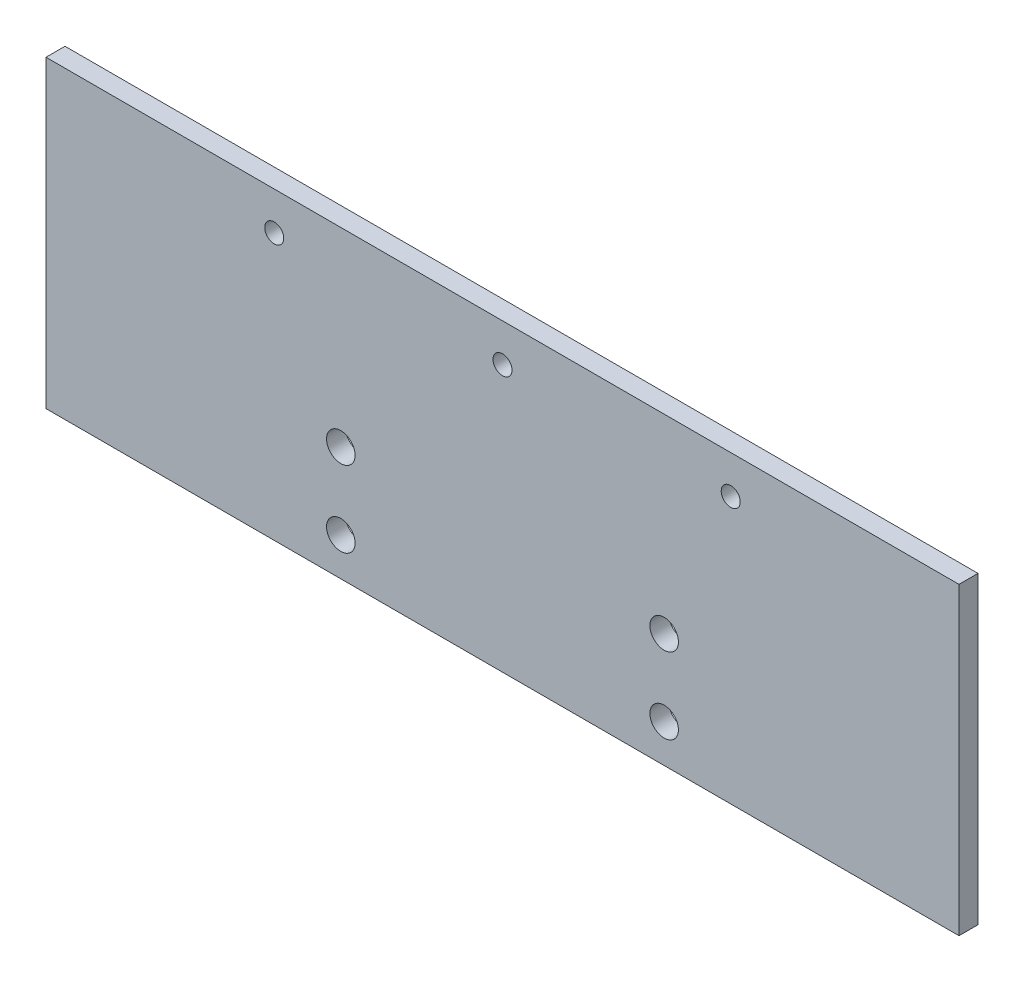
SolidWorks part; units mm, degrees
ref_plane "Front Plane" through (0, 0, 0) normal (0, 0, 1) x (1, 0, 0)
ref_plane "Top Plane" through (0, 0, 0) normal (0, 1, 0) x (1, 0, 0)
ref_plane "Right Plane" through (0, 0, 0) normal (1, 0, 0) x (0, 0, -1)
sketch "Sketch1" plane through (0, 0, 0) normal (0, 0, 1) x (1, 0, 0)
  line L1 (0, 0) -> (304.8, 0)
  line L2 (0, 0) -> (0, -101.6)
  line L3 (0, -101.6) -> (304.8, -101.6)
  line L4 (304.8, 0) -> (304.8, -101.6)
  dimension "D1" = 304.8
  dimension "D2" = 101.6
extrude "Boss-Extrude1" add sketch "Sketch1" along normal blind 6.35
sketch "Sketch2" plane through (0, 0, 6.35) normal (0, 0, 1) x (1, 0, 0)
  line L0 (304.8, 0) -> (0, 0) construction
  line L1 (0, 0) -> (0, -101.6) construction
  line L2 (0, -101.6) -> (304.8, -101.6) construction
  circle A0 centre (76.2, -12.7) radius 3.175
  circle A1 centre (152.4, -12.7) radius 3.175
  circle A2 centre (228.6, -12.7) radius 3.175
  circle A3 centre (98.425, -63.5) radius 4.7625
  circle A4 centre (206.375, -63.5) radius 4.7625
  circle A5 centre (98.425, -88.9) radius 4.7625
  circle A6 centre (206.375, -88.9) radius 4.7625
  dimension "D2" = 6.35
  dimension "D3" = 6.35
  dimension "D4" = 6.35
  dimension "D5" = 12.7
  dimension "D6" = 12.7
  dimension "D8" = 76.2
  dimension "D9" = 76.2
  dimension "D10" = 98.425
  dimension "D11" = 98.425
  dimension "D12" = 107.95
  dimension "D13" = 107.95
  dimension "D14" = 25.4
  dimension "D15" = 25.4
  dimension "D16" = 9.525
  dimension "D17" = 9.525
  dimension "D18" = 9.525
  dimension "D19" = 9.525
  dimension "D20" = 12.7
  dimension "D21" = 12.7
  dimension "D1" = 12.7
  dimension "D7" = 76.2
extrude "Cut-Extrude1" cut sketch "Sketch2" against normal blind 6.35
